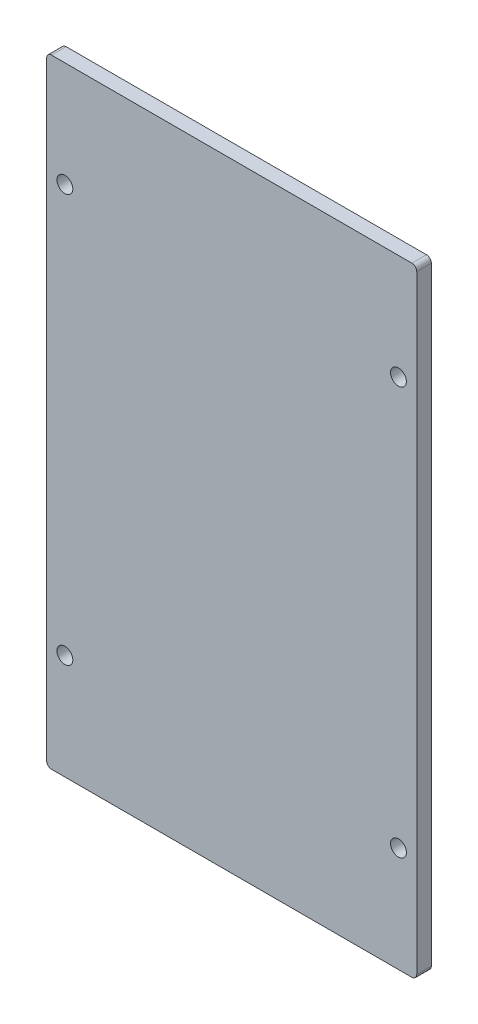
SolidWorks part; units mm, degrees
ref_plane "Front Plane" through (0, 0, 0) normal (0, 0, 1) x (1, 0, 0)
ref_plane "Top Plane" through (0, 0, 0) normal (0, 1, 0) x (1, 0, 0)
ref_plane "Right Plane" through (0, 0, 0) normal (1, 0, 0) x (0, 0, -1)
sketch "Sketch1" plane through (0, 0, 0) normal (0, 0, 1) x (1, 0, 0)
  line L0 (0, 63.5) -> (76, 63.5) construction
  line L1 (0, 0) -> (76, 0)
  line L2 (0, 0) -> (0, 127)
  line L3 (0, 127) -> (76, 127)
  line L4 (76, 0) -> (76, 127)
  line L10 (72.25, 21.625) -> (3.75, 21.625) construction
  line L15 (72.25, 21.625) -> (72.25, 105.375) construction
  line L16 (72.25, 105.375) -> (3.75, 105.375) construction
  line L17 (3.75, 21.625) -> (3.75, 105.375) construction
  line L18 (72.25, 21.625) -> (3.75, 105.375) construction
  line L19 (72.25, 105.375) -> (3.75, 21.625) construction
  circle A0 centre (3.75, 105.375) radius 1.625
  circle A1 centre (72.25, 105.375) radius 1.625
  circle A2 centre (72.25, 21.625) radius 1.625
  circle A3 centre (3.75, 21.625) radius 1.625
  point P7 (38, 63.5)
  dimension "D3" = 3.25
  dimension "D1" = 127
  dimension "D2" = 76
  dimension "D4" = 68.5
  dimension "D5" = 83.75
extrude "Boss-Extrude1" add sketch "Sketch1" along normal blind 3
fillet "Fillet1" radius 1 4 edges at (0, 0, 1.5) (76, 0, 1.5) (76, 127, 1.5) (0, 127, 1.5)
